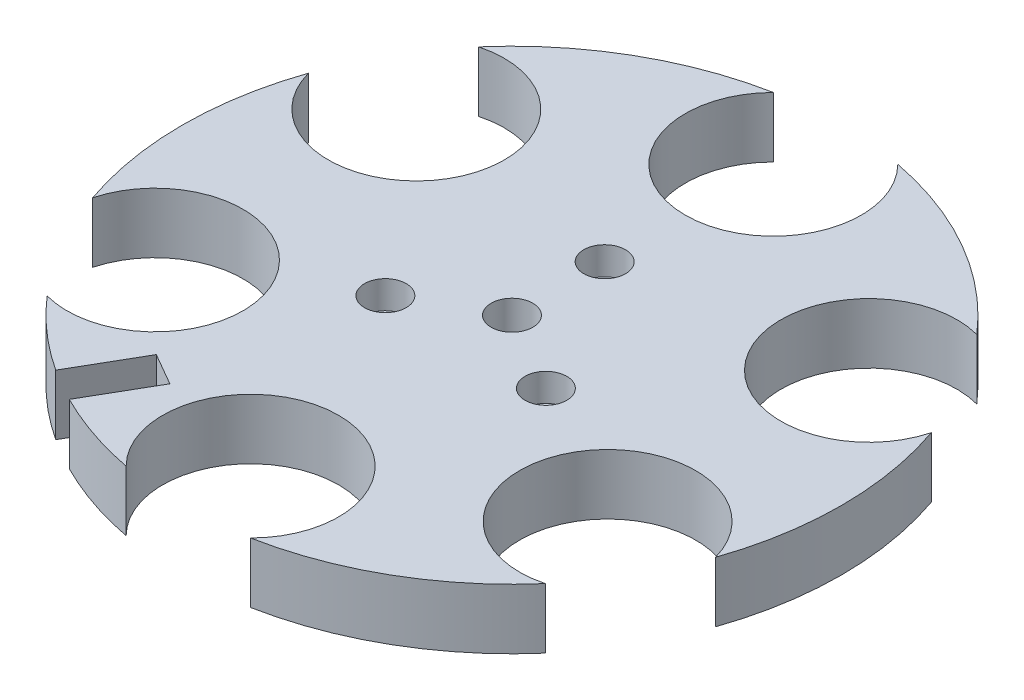
SolidWorks part; units mm, degrees
material "ABS"
ref_plane "Front Plane" through (0, 0, 0) normal (0, 0, 1) x (1, 0, 0)
ref_plane "Top Plane" through (0, 0, 0) normal (0, 1, 0) x (1, 0, 0)
ref_plane "Right Plane" through (0, 0, 0) normal (1, 0, 0) x (0, 0, -1)
sketch "Sketch1" plane through (0, 0, 0) normal (0, 1, 0) x (1, 0, 0)
  circle A0 centre (0, 0) radius 35.56
  dimension "D1" = 71.12
extrude "Boss-Extrude1" add sketch "Sketch1" along normal mid plane 6.5
sketch "Sketch2" plane through (0, 3.25, 0) normal (0, 1, 0) x (1, 0, 0)
  line L0 (0, 35.56) -> (0, -35.56) construction
  circle A0 centre (0, 0) radius 35.56 construction
  circle A1 centre (0, 28.2) radius 9.5
  point P7 (0, 0)
  dimension "D2" = 19
  dimension "D1" = 28.2
extrude "Cut-Extrude1" cut sketch "Sketch2" against normal through all
pattern_circular "CirPattern1" count 6 over 360 about axis through (0, 0, 0) along (0, 1, 0) of "Cut-Extrude1"
sketch "Sketch3" plane through (0, 3.25, 0) normal (0, 1, 0) x (1, 0, 0)
  line L0 (0, 18.7) -> (0, -18.7) construction
  arc A0 (-6.7148, 34.9203) -> (6.7148, 34.9203) centre (0, 28.2) ccw construction
  arc A1 (6.7148, -34.9203) -> (-6.7148, -34.9203) centre (0, -28.2) ccw construction
  circle A2 centre (0, 10) radius 2.25
  dimension "D2" = 4.5
  dimension "D1" = 10
extrude "Cut-Extrude2" cut sketch "Sketch3" against normal blind 3
pattern_circular "CirPattern2" count 3 over 360 about axis through (0, 0, 0) along (0, 1, 0) of "Cut-Extrude2"
sketch "Sketch4" plane through (0, 3.25, 0) normal (0, 1, 0) x (1, 0, 0)
  circle A0 centre (0, 0) radius 2.25
  dimension "D1" = 4.5
extrude "Cut-Extrude3" cut sketch "Sketch4" against normal through all both and the other way through all
sketch "Sketch5" plane through (0, -3.25, 0) normal (0, -1, 0) x (-1, 0, 0)
  line L0 (0, 18.7) -> (0, -18.7) construction
  arc A0 (-6.7148, 34.9203) -> (6.7148, 34.9203) centre (0, 28.2) ccw construction
  arc A1 (6.7148, -34.9203) -> (-6.7148, -34.9203) centre (0, -28.2) ccw construction
  circle A2 centre (0, 10) radius 2
  dimension "D2" = 4
  dimension "D1" = 10
extrude "Boss-Extrude2" add sketch "Sketch5" along normal blind 2.5
pattern_circular "CirPattern3" count 3 over 360 about axis through (0, 0, 0) along (0, 1, 0) of "Boss-Extrude2"
sketch "Sketch6" plane through (0, -3.25, 0) normal (0, -1, 0) x (1, 0, 0)
  line L0 (-17.78, 30.7959) -> (17.78, -30.7959) construction
  line L1 (-12.0479, 24.8677) -> (-15.5121, 22.8677)
  line L2 (-12.0479, 24.8677) -> (-16.0479, 31.7959)
  line L3 (-15.5121, 22.8677) -> (-19.5121, 29.7959)
  line L4 (-16.0479, 31.7959) -> (-19.5121, 29.7959)
  arc A0 (-6.7148, 34.9203) -> (-26.8845, 23.2753) centre (0, 0) ccw construction
  arc A1 (6.7148, -34.9203) -> (26.8845, -23.2753) centre (0, 0) ccw construction
  point P8 (-13.78, 23.8677)
  dimension "D1" = 4
  dimension "D2" = 8
extrude "Cut-Extrude4" cut sketch "Sketch6" against normal through all
